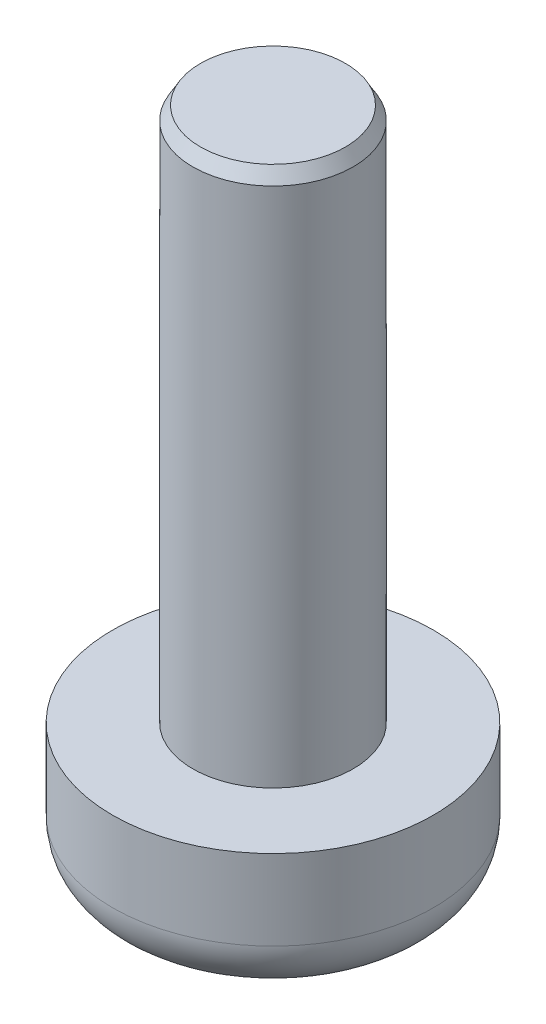
SolidWorks part; units mm, degrees
ref_plane "Front Plane" through (0, 0, 0) normal (0, 0, 1) x (1, 0, 0)
ref_plane "Top Plane" through (0, 0, 0) normal (0, 1, 0) x (1, 0, 0)
ref_plane "Right Plane" through (0, 0, 0) normal (1, 0, 0) x (0, 0, -1)
sketch "Sketch1" plane through (0, 0, 0) normal (0, 1, 0) x (1, 0, 0)
  circle A0 centre (0, 0) radius 1.5
extrude "Boss-Extrude1" add sketch "Sketch1" along normal blind 10
chamfer "Chamfer1" distance 0.25 angle 30 1 edges at (0, 10, 1.5)
sketch "Sketch2" plane through (0, 0, 0) normal (0, -1, 0) x (-1, 0, 0)
  circle A0 centre (0, 0) radius 3
extrude "Boss-Extrude2" add sketch "Sketch2" along normal blind 2.5
fillet "Fillet1" radius 1 1 edges at (0, -2.5, -3)
sketch "Sketch3" plane through (0, -2.5, 0) normal (0, -1, 0) x (-1, 0, 0)
  line L1 (1.5877, 0) -> (0.7939, 1.375)
  line L2 (0.7939, 1.375) -> (-0.7939, 1.375)
  line L3 (-0.7939, 1.375) -> (-1.5877, 0)
  line L4 (-1.5877, 0) -> (-0.7939, -1.375)
  line L5 (-0.7939, -1.375) -> (0.7939, -1.375)
  line L6 (0.7939, -1.375) -> (1.5877, 0)
  circle A0 centre (0, 0) radius 1.375 construction
extrude "Cut-Extrude1" cut sketch "Sketch3" against normal blind 2
